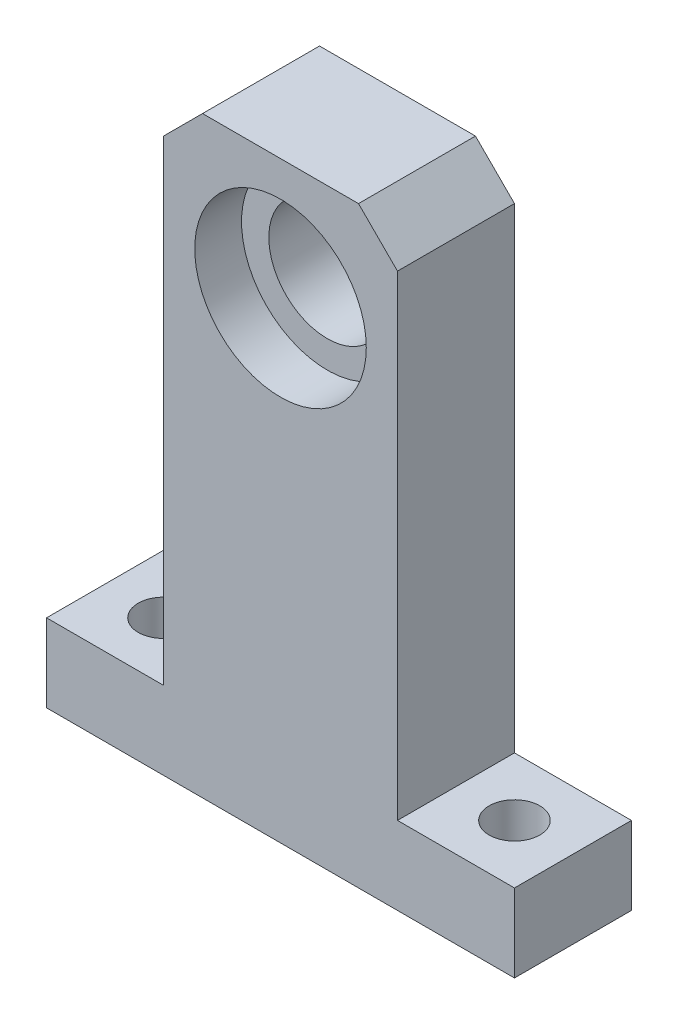
SolidWorks part; units mm, degrees
material "6061 合金"
ref_plane "前视基准面" through (0, 0, 0) normal (0, 0, 1) x (1, 0, 0)
ref_plane "上视基准面" through (0, 0, 0) normal (0, 1, 0) x (1, 0, 0)
ref_plane "右视基准面" through (0, 0, 0) normal (1, 0, 0) x (0, 0, -1)
sketch "草图1" plane through (0, 0, 0) normal (0, 0, 1) x (1, 0, 0)
  line L1 (-30, 38) -> (30, 38)
  line L2 (-30, 38) -> (-30, -38)
  line L3 (-30, -38) -> (30, -38)
  line L4 (30, 38) -> (30, -38)
  line L5 (-30, 38) -> (30, -38) construction
  line L6 (-30, -38) -> (30, 38) construction
  point P0 (0, 0)
  dimension "D1" = 60
  dimension "D2" = 76
extrude "拉伸1" add sketch "草图1" along normal mid plane 15
sketch "草图2" plane through (0, 0, 7.5) normal (0, 0, 1) x (1, 0, 0)
  line L0 (-30, -38) -> (30, -38) construction
  line L1 (-30, 38) -> (-15, 38)
  line L2 (-30, 38) -> (-30, -28)
  line L3 (-30, -28) -> (-15, -28)
  line L4 (-15, 38) -> (-15, -28)
  line L5 (30, 38) -> (-30, 38) construction
  line L6 (30, 38) -> (15, 38)
  line L7 (30, 38) -> (30, -28)
  line L8 (30, -28) -> (15, -28)
  line L9 (15, 38) -> (15, -28)
  dimension "D1" = 10
  dimension "D2" = 15
extrude "拉伸2" cut sketch "草图2" against normal through all
chamfer "倒角1" distance 5 angle 45 2 edges at (15, 38, 0) (-15, 38, 0)
hole_wizard "Ø6.5 (6.5) 直径孔1" positions "草图5" profile "草图4" hole size "Ø6.5" standard "ISO"
sketch "草图5" plane through (0, -38, 0) normal (0, -1, 0) x (1, 0, 0)
  point P0 (-22.5, 0)
  point P1 (22.5, 0)
  dimension "D1" = 45
  dimension "D2" = 22.5
sketch "草图4" plane through (-22.5, -38, 0) normal (1, 0, 0) x (0, 0, -1)
  line L0 (0, 0) -> (0, 16.9528)
  line L1 (0, 16.9528) -> (3.25, 15)
  line L2 (3.25, 15) -> (3.25, 0)
  line L5 (3.25, 0) -> (0, 0)
  line L10 (0, 16.9528) -> (-3.25, 15) construction
  line L11 (0, -6.35) -> (0, 107.95) construction
  dimension "孔直径" = 6.5
  dimension "孔深度" = 15
  dimension "导头角度" = 118
sketch "草图6" plane through (0, 0, 7.5) normal (0, 0, 1) x (1, 0, 0)
  line L0 (-30, -38) -> (30, -38) construction
  circle A0 centre (0, 22.5) radius 7.5
  dimension "D1" = 15
  dimension "D2" = 60.5
extrude "拉伸4" cut sketch "草图6" against normal through all
sketch "草图7" plane through (0, 0, 7.5) normal (0, 0, 1) x (1, 0, 0)
  circle A0 centre (0, 22.5) radius 11
  dimension "D1" = 22
extrude "拉伸5" cut sketch "草图7" against normal blind 6
